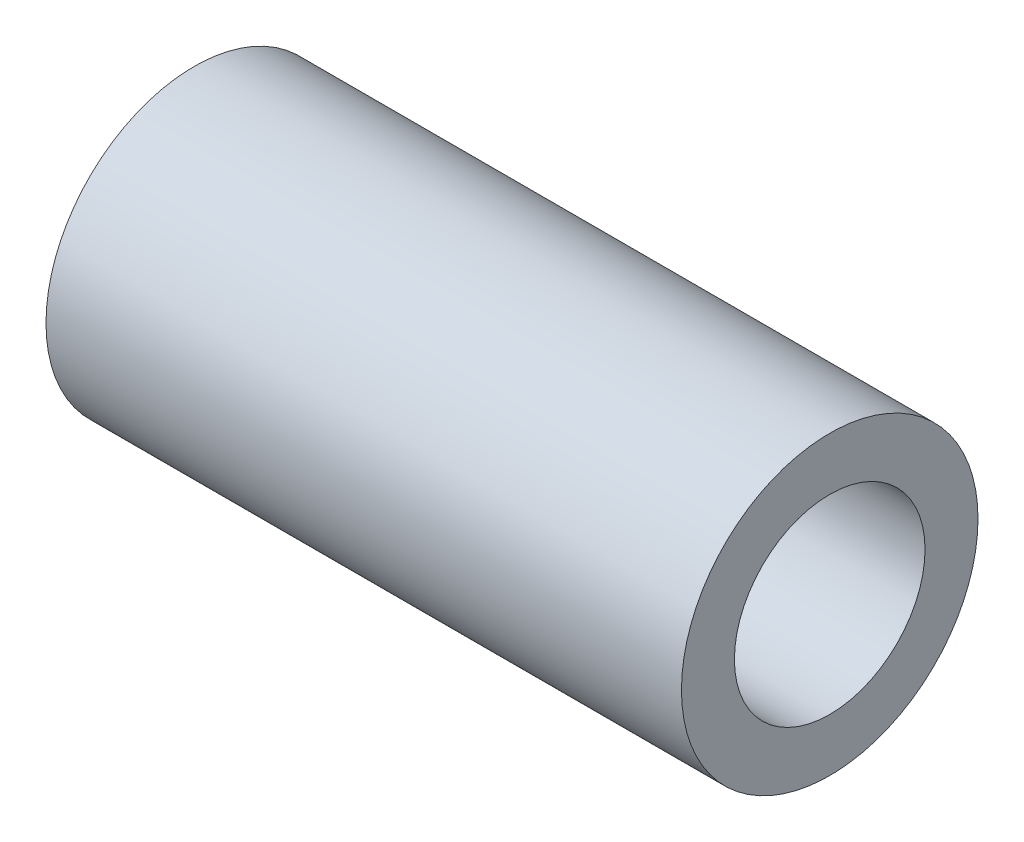
SolidWorks part; units mm, degrees
ref_plane "Front" through (0, 0, 0) normal (0, 0, 1) x (1, 0, 0)
ref_plane "Top" through (0, 0, 0) normal (0, 1, 0) x (1, 0, 0)
ref_plane "Right" through (0, 0, 0) normal (1, 0, 0) x (0, 0, -1)
sketch "Sketch1" plane through (0, 0, 0) normal (0, 0, 1) x (1, 0, 0)
  line L0 (0, 0.2286) -> (0, 0.3556)
  line L1 (0, 0.3556) -> (-1.524, 0.3556)
  line L2 (-1.524, 0.3556) -> (-1.524, 0.2286)
  line L3 (-1.524, 0.2286) -> (0, 0.2286)
  line L4 (-1.524, 0) -> (0, 0) construction
  dimension "D1" = 1.524
  dimension "D2" = 0.2286
  dimension "D3" = 0.3556
revolve "Revolve1" add sketch "Sketch1" angle 360 about L4
ref_plane "Plane1" through (-1.024, 0, 0) normal (-1, 0, 0) x (0, 0, 1)
ref_point "Point1"
ref_plane "Plane2" through (-0.5, 0, 0) normal (1, 0, 0) x (0, 0, -1)
ref_point "Point2"
